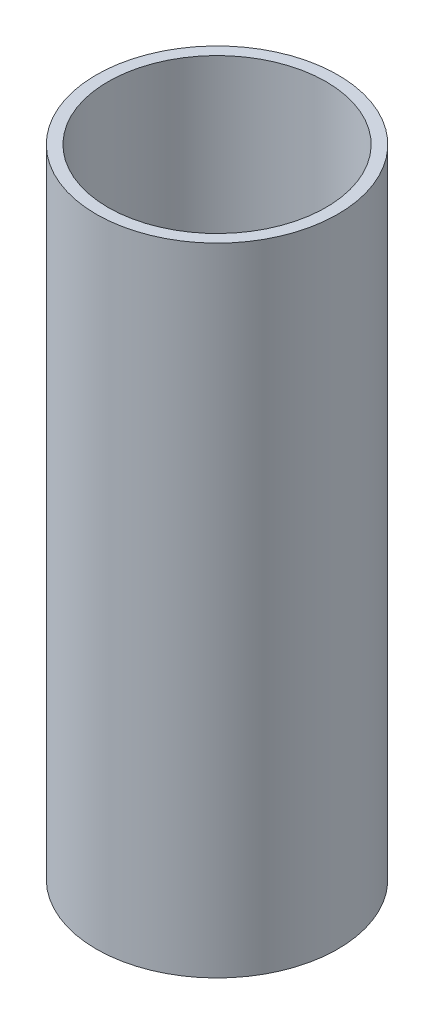
SolidWorks part; units mm, degrees
material "A-Glass Fiber"
ref_plane "Front Plane" through (0, 0, 0) normal (0, 0, 1) x (1, 0, 0)
ref_plane "Top Plane" through (0, 0, 0) normal (0, 1, 0) x (1, 0, 0)
ref_plane "Right Plane" through (0, 0, 0) normal (1, 0, 0) x (0, 0, -1)
sketch "Sketch1" plane through (0, 0, 0) normal (0, 1, 0) x (1, 0, 0)
  circle A0 centre (0, 0) radius 19.2786
  circle A1 centre (0, 0) radius 17.399
  dimension "D1" = 38.5572
  dimension "D2" = 34.798
extrude "Boss-Extrude1" add sketch "Sketch1" along normal blind 101.6 contours A1 | A0
equation "\"Length\"=4"
equation "\"D1@Boss-Extrude1\"=\"Length\""
